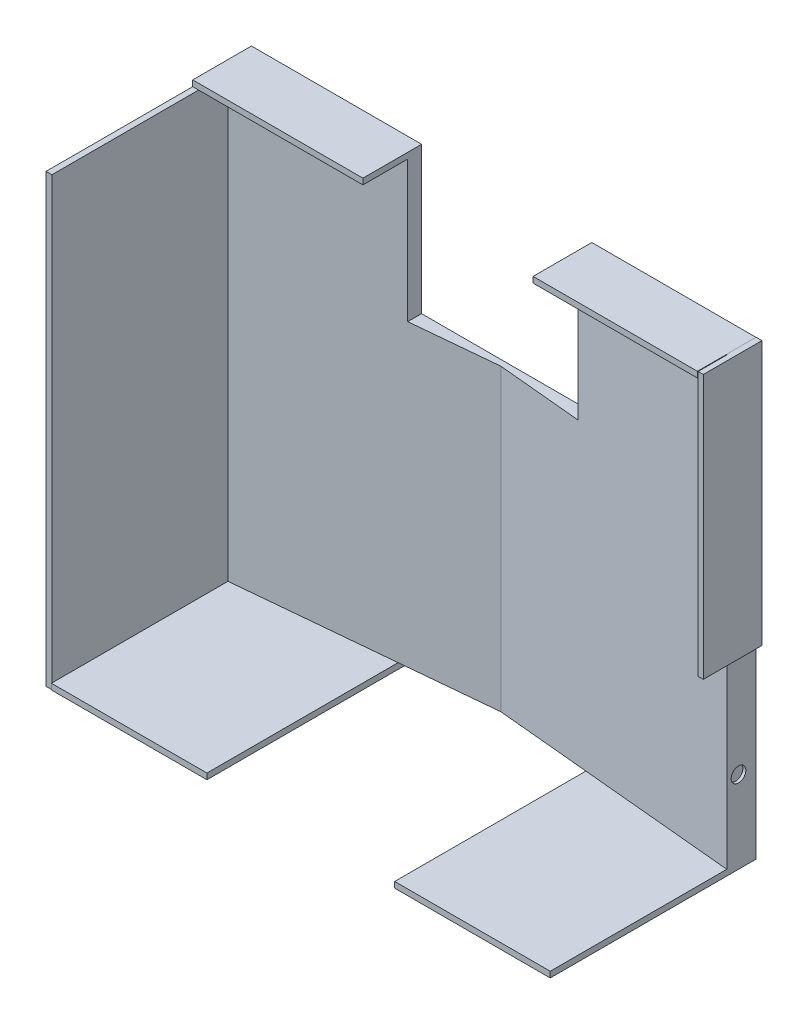
SolidWorks part; units mm, degrees
ref_plane "Plan de face" through (0, 0, 0) normal (0, 0, 1) x (1, 0, 0)
ref_plane "Plan de dessus" through (0, 0, 0) normal (0, 1, 0) x (1, 0, 0)
ref_plane "Plan de droite" through (0, 0, 0) normal (1, 0, 0) x (0, 0, -1)
sketch "Esquisse1" plane through (0, 0, 0) normal (0, 0, 1) x (1, 0, 0)
  line L0 (-29, 75) -> (-29, 27)
  line L1 (-85, 75) -> (85, 75)
  line L2 (-85, 75) -> (-85, -75)
  line L3 (-85, -75) -> (85, -75)
  line L4 (85, 75) -> (85, -75)
  line L5 (-85, 75) -> (85, -75) construction
  line L6 (-85, -75) -> (85, 75) construction
  line L7 (-29, 75) -> (29, 75)
  line L8 (-29, 27) -> (29, 27)
  line L9 (29, 75) -> (29, 27)
  point P0 (0, 0)
  dimension "D1" = 170
  dimension "D2" = 150
  dimension "D3" = 58
  dimension "D4" = 48
  dimension "D5" = 56
  dimension "D6" = 56
extrude "Boss.-Extru.1" add sketch "Esquisse1" along normal blind 10 contours L1 L9 L8 L0 L2 L3 L4
sketch "Esquisse5" plane through (0, -75, 0) normal (0, -1, 0) x (1, 0, 0)
  line L0 (-85, 10) -> (85, 10)
  line L1 (-85, 10) -> (-85, 1.5095)
  line L2 (85, 10) -> (85, 1.5095)
  line L3 (-85, 0) -> (85, 0)
  line L4 (-85, 10) -> (0, 2)
  line L6 (0, 2) -> (85, 10)
  point P9 (0, 2)
  dimension "D1" = 170
  dimension "D2" = 2
  dimension "D3" = 10
extrude "Enlèv. mat.-Extru.1" cut sketch "Esquisse5" against normal through all
sketch "Esquisse6" plane through (0, -75, 0) normal (0, -1, 0) x (-1, 0, 0)
  line L0 (85, 0) -> (-85, 0)
  line L1 (85, 0) -> (85, -20.1675)
  line L2 (-85, 0) -> (-85, -20.1675)
  line L3 (85, -20.1675) -> (-85, -20.1675)
extrude "Boss.-Extru.2" add sketch "Esquisse6" along normal blind 2
sketch "Esquisse8" plane through (0, 0, 20.1675) normal (0, 0, 1) x (1, 0, 0)
  line L0 (-85, -75) -> (-85, -77)
  line L1 (-85, -75) -> (100.0015, -75)
  line L2 (-85, -77) -> (100.0015, -77)
  line L3 (100.0015, -75) -> (100.0015, -77)
extrude "Boss.-Extru.3" add sketch "Esquisse8" along normal blind 50
sketch "Esquisse9" plane through (-85, 0, 0) normal (-1, 0, 0) x (0, 0, 1)
  line L0 (0, -77) -> (0, 75)
  line L1 (0, -77) -> (70, -77)
  line L2 (0, 75) -> (70, 75)
  line L3 (70, -77) -> (70, 75)
  dimension "D1" = 70
extrude "Boss.-Extru.4" add sketch "Esquisse9" along normal blind 2
sketch "Esquisse10" plane through (85, 0, 0) normal (1, 0, 0) x (0, 0, -1)
  line L0 (0, -77) -> (0, 75)
  line L1 (0, -77) -> (-69.9475, -77)
  line L2 (0, 75) -> (-69.9475, 75)
  line L3 (-69.9475, -77) -> (-69.9475, 75)
extrude "Boss.-Extru.5" add sketch "Esquisse10" along normal blind 2
sketch "Esquisse11" plane through (0, 75, 0) normal (0, 1, 0) x (1, 0, 0)
  line L0 (-87, 0) -> (-29, 0)
  line L1 (-87, 0) -> (-87, -20)
  line L2 (-29, 0) -> (-29, -20)
  line L3 (-87, -20) -> (-29, -20)
  line L4 (87, 0) -> (29, 0)
  line L5 (87, 0) -> (87, -20)
  line L6 (29, 0) -> (29, -20)
  line L7 (87, -20) -> (29, -20)
  dimension "D1" = 20
  dimension "D2" = 20
extrude "Boss.-Extru.6" add sketch "Esquisse11" along normal blind 2
sketch "Esquisse19" plane through (0, -77, 0) normal (0, -1, 0) x (-1, 0, 0)
  line L0 (-32, 0) -> (-32, -70.1675)
  line L1 (-32, 0) -> (32, 0)
  line L2 (-32, -70.1675) -> (32, -70.1675)
  line L3 (32, 0) -> (32, -70.1675)
  line L4 (87, 0) -> (-87, 0) construction
  line L5 (85, -70.1675) -> (-100.0015, -70.1675) construction
  dimension "D1" = 32
  dimension "D2" = 32
extrude "Enlèv. mat.-Extru.9" cut sketch "Esquisse19" against normal blind 2
sketch "Esquisse24" plane through (87, 0, 0) normal (1, 0, 0) x (0, 0, -1)
  line L0 (-20.1675, -77) -> (0, -77) construction
  line L2 (0, -77) -> (0, 77) construction
  circle A0 centre (-6, -49) radius 2.5
  point P0 (-6, -49)
  dimension "D3" = 5
  dimension "D1" = 28
  dimension "D2" = 6
extrude "Enlèv. mat.-Extru.10" cut sketch "Esquisse24" against normal blind 3
sketch "Esquisse25" plane through (-87, 0, 0) normal (-1, 0, 0) x (0, 0, 1)
  line L0 (0, 77) -> (0, -77) construction
  line L2 (0, -77) -> (70, -77) construction
  line L4 (6, -51.8868) -> (8.5, -50.4434)
  line L5 (8.5, -50.4434) -> (8.5, -47.5566)
  line L6 (8.5, -47.5566) -> (6, -46.1132)
  line L7 (6, -46.1132) -> (3.5, -47.5566)
  line L8 (3.5, -47.5566) -> (3.5, -50.4434)
  line L9 (3.5, -50.4434) -> (6, -51.8868)
  circle A0 centre (6, -49) radius 2.5 construction
  point P0 (6, -49)
  dimension "D1" = 6
  dimension "D2" = 28
extrude "Enlèv. mat.-Extru.11" cut sketch "Esquisse25" against normal blind 3
sketch "Esquisse27" plane through (0, -75, 0) normal (0, 1, 0) x (1, 0, 0)
  line L0 (87, -20.1675) -> (100.0015, -20.1675)
  line L1 (87, -20.1675) -> (87, -70.2118)
  line L2 (100.0015, -20.1675) -> (100.0015, -70.2118)
  line L3 (87, -70.2118) -> (100.0015, -70.2118)
extrude "Enlèv. mat.-Extru.12" cut sketch "Esquisse27" against normal through all
sketch "Esquisse28" plane through (87, 0, 0) normal (1, 0, 0) x (0, 0, -1)
  line L0 (0, -77) -> (0, 77)
  line L1 (0, -77) -> (-70.1692, -77)
  line L2 (0, 77) -> (-70.1692, 77)
  line L3 (-70.1692, -77) -> (-70.1692, 77)
extrude "Enlèv. mat.-Extru.13" cut sketch "Esquisse28" against normal blind 2
sketch "Esquisse29" plane through (85, 0, 0) normal (1, 0, 0) x (0, 0, -1)
  line L0 (0, -12.9482) -> (-10, -12.9482)
  line L1 (0, -12.9482) -> (0, 77.0518)
  line L2 (-10, -12.9482) -> (-10, 77.0518)
  line L3 (0, 77.0518) -> (-10, 77.0518)
  line L4 (0, -77) -> (0, 77) construction
  line L5 (-10, 75) -> (-10, -75) construction
  dimension "D1" = 90
extrude "Boss.-Extru.7" add sketch "Esquisse29" along normal blind 2
sketch "Esquisse30" plane through (0, 0, 10) normal (0, 0, 1) x (1, 0, 0)
  line L0 (87, 77.0518) -> (87, -12.9482)
  line L1 (87, 77.0518) -> (85.2361, 77.0518)
  line L2 (87, -12.9482) -> (85.2361, -12.9482)
  line L3 (85.2361, 77.0518) -> (85.2361, -12.9482)
extrude "Boss.-Extru.8" add sketch "Esquisse30" along normal blind 10
